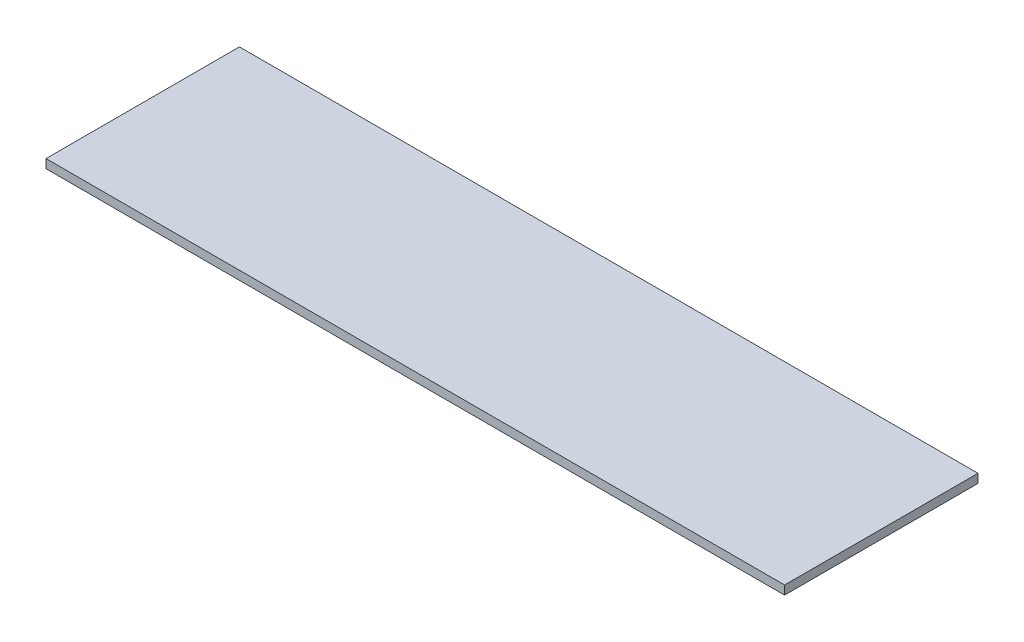
SolidWorks part; units mm, degrees
ref_plane "Front Plane" through (0, 0, 0) normal (0, 0, 1) x (1, 0, 0)
ref_plane "Top Plane" through (0, 0, 0) normal (0, 1, 0) x (1, 0, 0)
ref_plane "Right Plane" through (0, 0, 0) normal (1, 0, 0) x (0, 0, -1)
sketch "Sketch1" plane through (0, 0, 0) normal (0, 1, 0) x (1, 0, 0)
  line L0 (0, 0) -> (133.35, 0)
  line L1 (133.35, 0) -> (133.35, 34.925)
  line L2 (133.35, 34.925) -> (0, 34.925)
  line L3 (0, 34.925) -> (0, 0)
  dimension "D1" = 34.925
  dimension "D2" = 133.35
extrude "Boss-Extrude1" add sketch "Sketch1" along normal blind 1.5875
